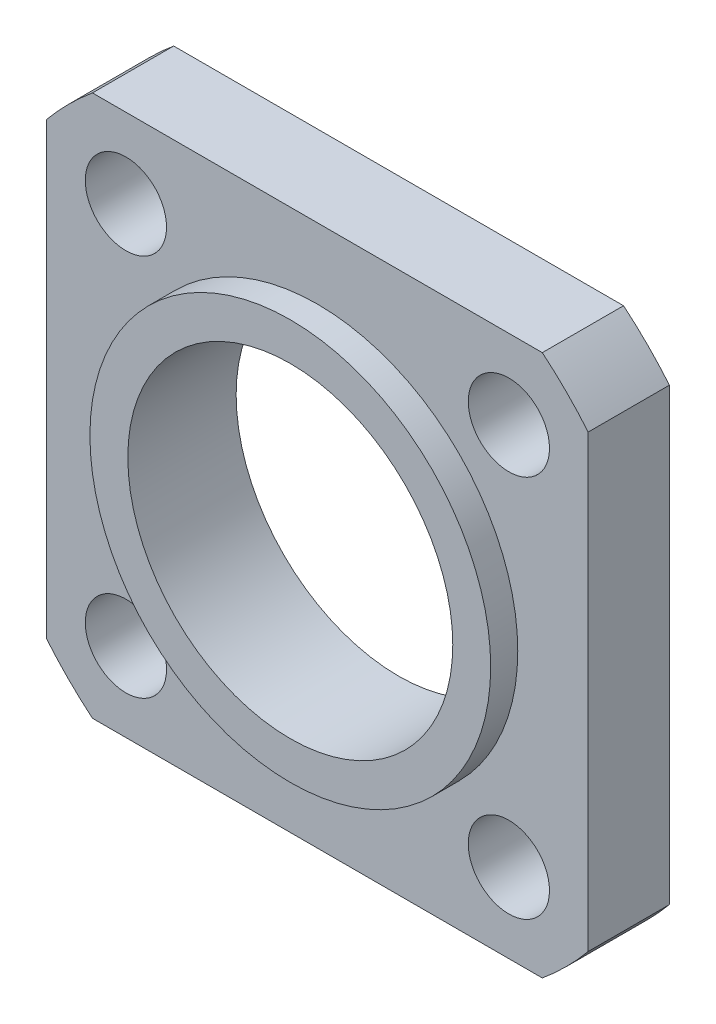
SolidWorks part; units mm, degrees
material "6061 合金"
ref_plane "前视基准面" through (0, 0, 0) normal (0, 0, 1) x (1, 0, 0)
ref_plane "上视基准面" through (0, 0, 0) normal (0, 1, 0) x (1, 0, 0)
ref_plane "右视基准面" through (0, 0, 0) normal (1, 0, 0) x (0, 0, -1)
other "Configuration Table"
sketch "草图1" plane through (0, 0, 0) normal (0, 0, 1) x (1, 0, 0)
  line L0 (-7.0711, 7.0711) -> (0, 0) construction
  line L1 (0, 0) -> (-10, 0) construction
  circle A0 centre (0, 0) radius 10 construction
  circle A1 centre (0, 0) radius 13
  circle A2 centre (0, 0) radius 6
  circle A3 centre (-7.0711, 7.0711) radius 1.5
  circle A4 centre (7.0711, 7.0711) radius 1.5
  circle A5 centre (7.0711, -7.0711) radius 1.5
  circle A6 centre (-7.0711, -7.0711) radius 1.5
  point P17 (0, 0)
  dimension "D1" = 20
  dimension "D2" = 26
  dimension "D3" = 12
  dimension "D5" = 3
  dimension "D4" = 45
  dimension "D6" = 4
extrude "凸台-拉伸1" add sketch "草图1" along normal blind 3
sketch "草图2" plane through (0, 0, 3) normal (0, 0, 1) x (1, 0, 0)
  circle A0 centre (0, 0) radius 7.4
  circle A1 centre (0, 0) radius 6
  dimension "D1" = 14.8
  dimension "D2" = 12
extrude "凸台-拉伸2" add sketch "草图2" along normal blind 1
sketch "草图3" plane through (0, 0, 3) normal (0, 0, 1) x (1, 0, 0)
  line L0 (-8.3066, 10) -> (8.3066, 10)
  line L1 (10, 8.3066) -> (10, -8.3066)
  line L2 (8.3066, -10) -> (-8.3066, -10)
  line L3 (-10, -8.3066) -> (-10, 8.3066)
  circle A0 centre (0, 0) radius 13 construction
  arc A2 (-10, 8.3066) -> (-10, -8.3066) centre (0, 0) ccw
  arc A3 (8.3066, 10) -> (-8.3066, 10) centre (0, 0) ccw
  arc A4 (10, -8.3066) -> (10, 8.3066) centre (0, 0) ccw
  arc A5 (-8.3066, -10) -> (8.3066, -10) centre (0, 0) ccw
  point P16 (0, 0)
  dimension "D1" = 10
  dimension "D2" = 4
extrude "切除-拉伸1" cut sketch "草图3" against normal blind 41
